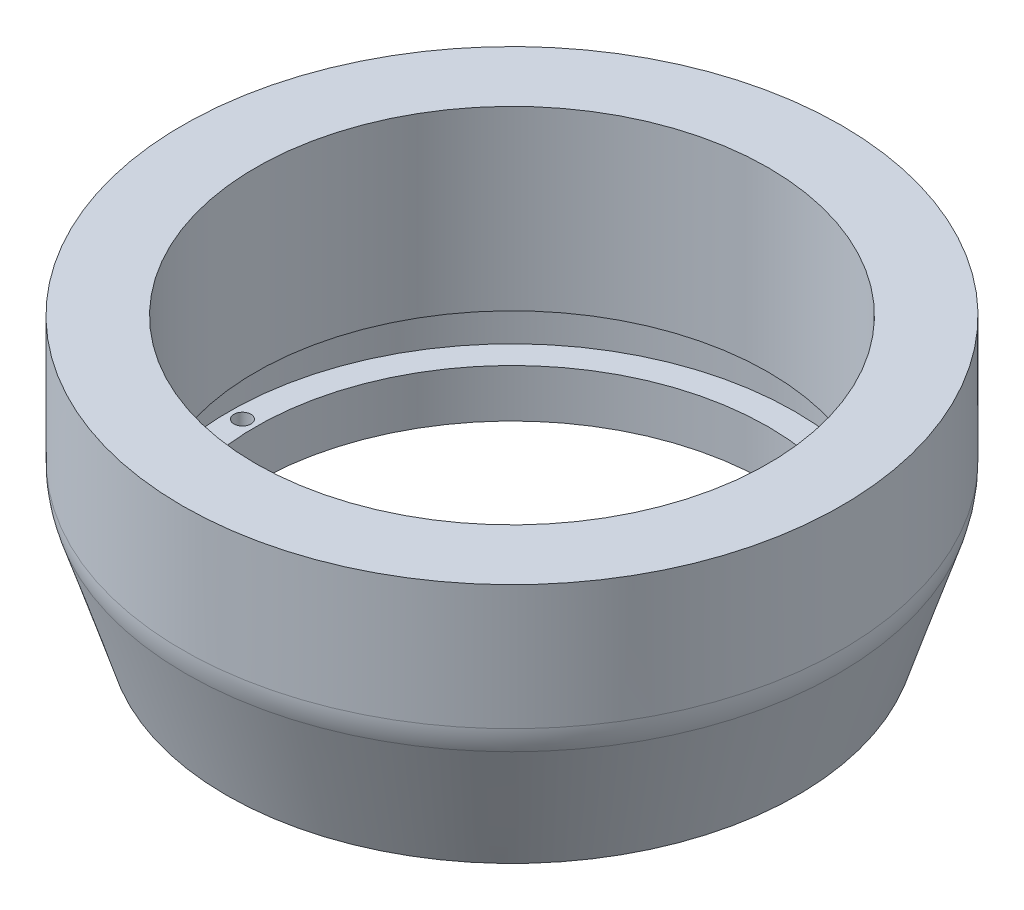
SolidWorks part; units mm, degrees
ref_plane "Front Plane" through (0, 0, 0) normal (0, 0, 1) x (1, 0, 0)
ref_plane "Top Plane" through (0, 0, 0) normal (0, 1, 0) x (1, 0, 0)
ref_plane "Right Plane" through (0, 0, 0) normal (1, 0, 0) x (0, 0, -1)
sketch "Sketch1" plane through (0, 0, 0) normal (0, 1, 0) x (1, 0, 0)
  circle A0 centre (0, 0) radius 35
  circle A1 centre (0, 0) radius 45
  dimension "D1" = 70
  dimension "D2" = 90
extrude "Boss-Extrude1" add sketch "Sketch1" along normal blind 37.21
sketch "Sketch2" plane through (0, 0, 0) normal (1, 0, 0) x (0, 0, -1)
  line L3 (45, 18.605) -> (39.0049, 0)
  line L4 (39.0049, 0) -> (45, 0)
  line L6 (45, 0) -> (45, 37.21) construction
  line L12 (45, 0) -> (45, 18.605)
revolve "Cut-Revolve2" cut sketch "Sketch2" angle 360 about axis through (0, 37.21, 0) along (0, -1, 0)
fillet "Fillet1" radius 10 1 edges at (0, 18.605, 45)
sketch "Sketch3" plane through (0, 0, 0) normal (1, 0, 0) x (0, 0, -1)
  line L0 (-35, 37.21) -> (-35, 47.0391) construction
  line L2 (-35, 13.0327) -> (-38.6234, 13.0327)
  line L3 (-35, 13.0327) -> (-35, 6.5671)
  line L4 (-35, 6.5671) -> (-38.6234, 6.5671)
  line L5 (-38.6234, 13.0327) -> (-38.6234, 6.5671)
revolve "Cut-Revolve3" cut sketch "Sketch3" angle 360 about axis through (0, 37.21, 0) along (0, -1, 0)
sketch "Sketch4" plane through (0, 0, 0) normal (0, -1, 0) x (-1, 0, 0)
  circle A0 centre (36.8055, 0) radius 1.1619
  point P2 (36.8055, 0)
extrude "Cut-Extrude3" cut sketch "Sketch4" against normal blind 10 and the other way through all
sketch "Sketch5" plane through (0, 0, 0) normal (0, -1, 0) x (-1, 0, 0)
  circle A0 centre (-36.7718, 0) radius 1.2223
extrude "Cut-Extrude4" cut sketch "Sketch5" against normal blind 10
